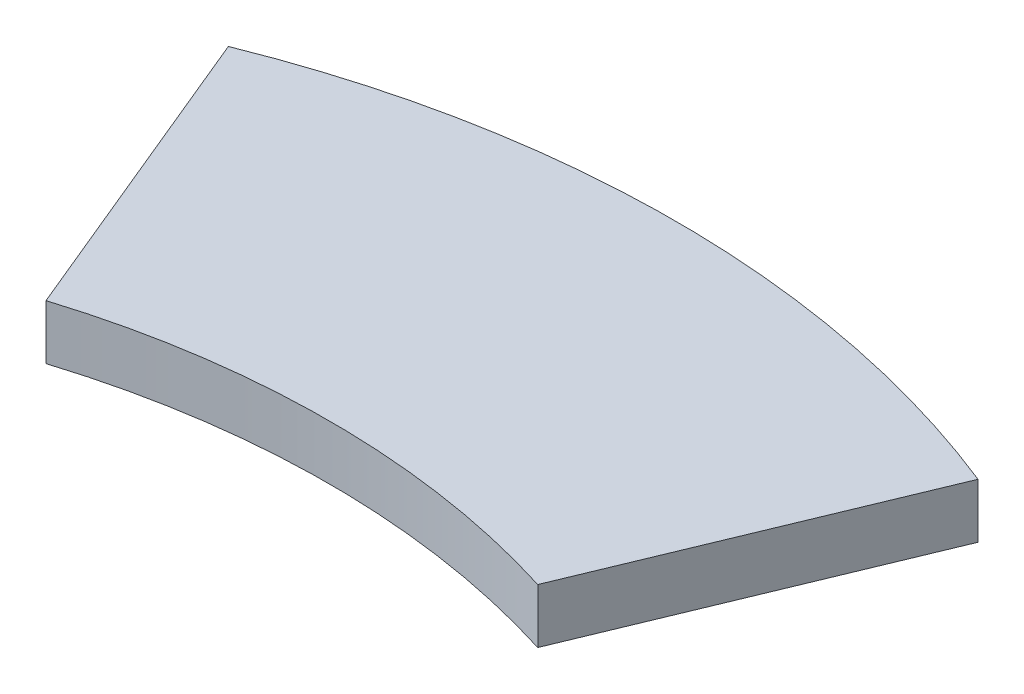
SolidWorks part; units mm, degrees
material "Chrome Stainless Steel"
ref_plane "Front Plane" through (0, 0, 0) normal (0, 0, 1) x (1, 0, 0)
ref_plane "Top Plane" through (0, 0, 0) normal (0, 1, 0) x (1, 0, 0)
ref_plane "Right Plane" through (0, 0, 0) normal (1, 0, 0) x (0, 0, -1)
sketch "Sketch2" plane through (0, 0, 0) normal (0, 1, 0) x (1, 0, 0)
  line L0 (-45.1884, -35.608) -> (-69.556, 23.2206) construction
  line L1 (46.0764, -35.608) -> (70.444, 23.2206) construction
  line L2 (-44.6154, -34.3782) -> (-68.2462, 22.6717)
  line L3 (45.5034, -34.3782) -> (69.1343, 22.6717)
  arc A0 (-45.1884, -35.608) -> (46.0764, -35.608) centre (0.444, -178.4984) cw construction
  arc A1 (70.444, 23.2206) -> (-69.556, 23.2206) centre (0.444, -148.4984) ccw construction
  arc A2 (69.1343, 22.6717) -> (-68.2462, 22.6717) centre (0.444, -148.4984) ccw
  arc A3 (-44.6154, -34.3782) -> (45.5034, -34.3782) centre (0.444, -178.4984) cw
  dimension "D1" = 1
extrude "Boss-Extrude1" add sketch "Sketch2" along normal mid plane 10
